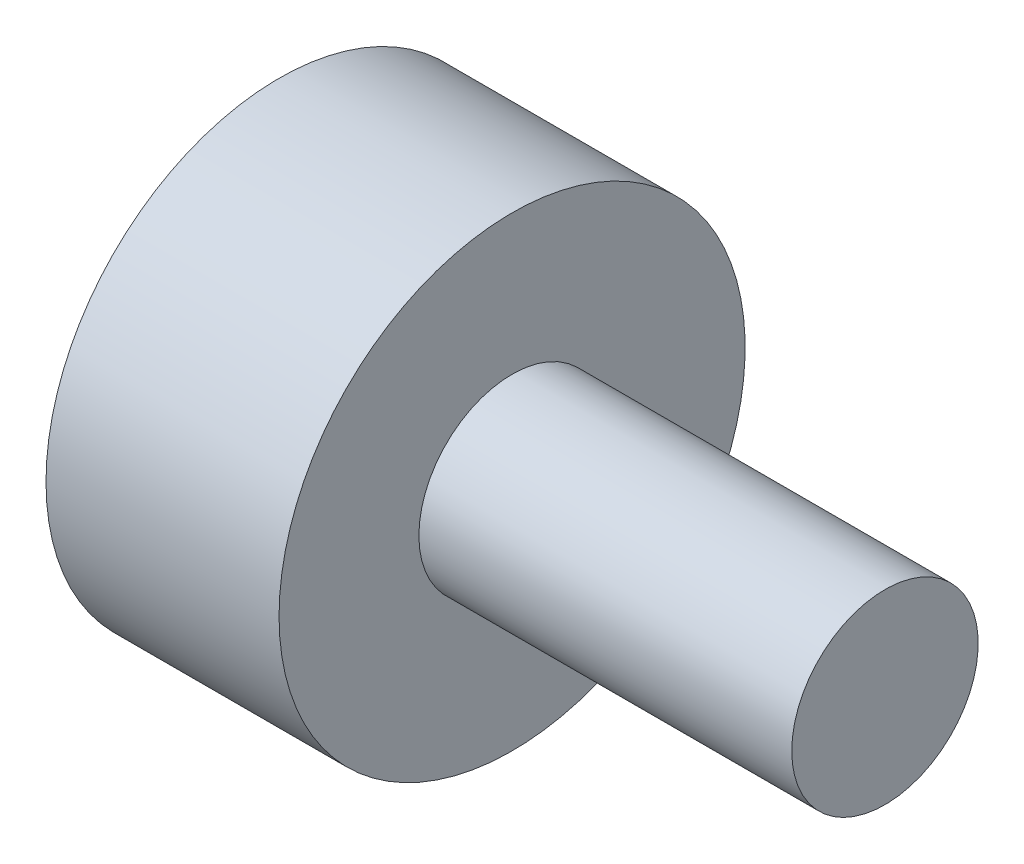
SolidWorks part; units mm, degrees
ref_plane "Front Plane" through (0, 0, 0) normal (0, 0, 1) x (1, 0, 0)
ref_plane "Top Plane" through (0, 0, 0) normal (0, 1, 0) x (1, 0, 0)
ref_plane "Right Plane" through (0, 0, 0) normal (1, 0, 0) x (0, 0, -1)
sketch "Sketch1" plane through (0, 0, 0) normal (0, 0, 1) x (1, 0, 0)
  line L0 (0, 12) -> (0, 25)
  line L1 (0, 25) -> (25, 25)
  line L2 (25, 25) -> (25, 10)
  line L3 (25, 10) -> (65, 10)
  line L4 (65, 10) -> (65, 0)
  line L5 (65, 0) -> (40, 0)
  line L6 (40, 0) -> (40, 7)
  line L7 (40, 7) -> (12, 7)
  line L8 (12, 7) -> (12, 12)
  line L9 (12, 12) -> (0, 12)
  line L10 (0, 0) -> (70, 0) construction
revolve "Revolve1" add sketch "Sketch1" angle 360 about L10
